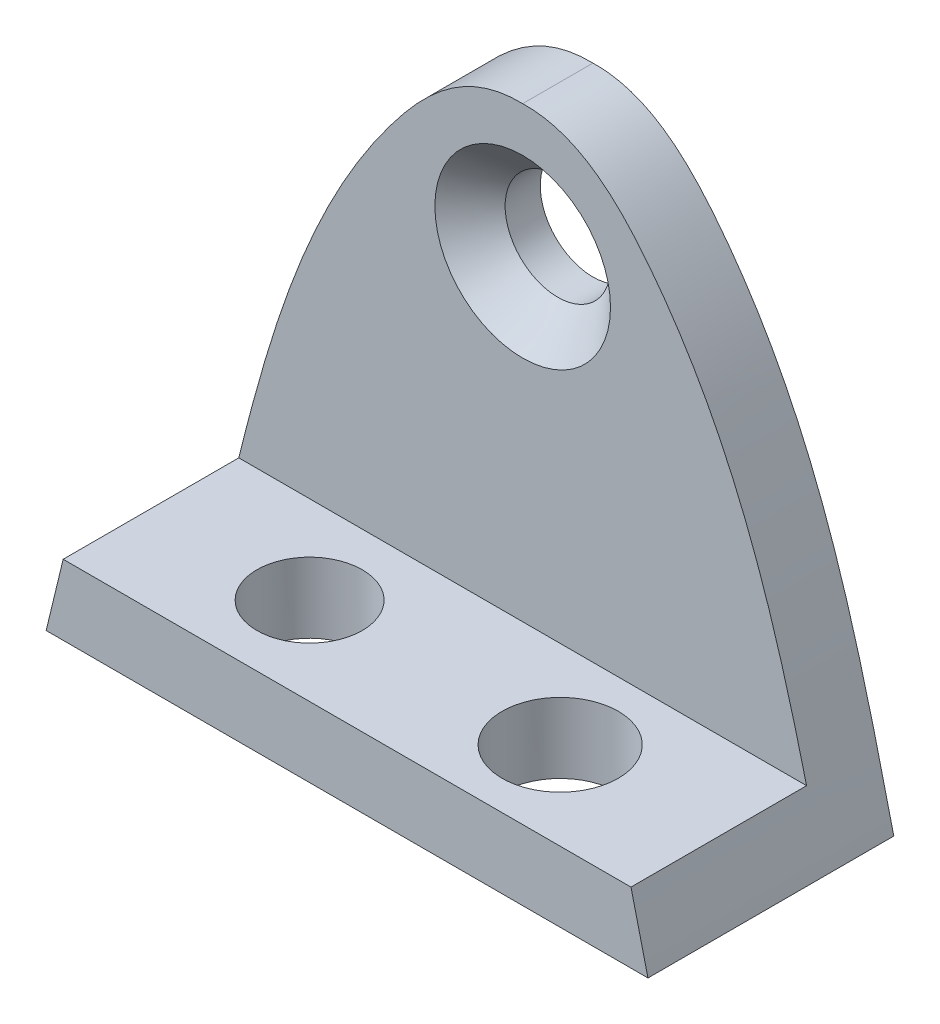
SolidWorks part; units mm, degrees
ref_plane "Front Plane" through (0, 0, 0) normal (0, 0, 1) x (1, 0, 0)
ref_plane "Top Plane" through (0, 0, 0) normal (0, 1, 0) x (1, 0, 0)
ref_plane "Right Plane" through (0, 0, 0) normal (1, 0, 0) x (0, 0, -1)
sketch "Sketch1" plane through (0, 0, 0) normal (0, 0, 1) x (1, 0, 0)
  line L0 (0, -1.5) -> (-1.5, -1.5) construction
  line L1 (0, -11) -> (-1.5, -11) construction
  line L2 (8.5669, -11) -> (-8.5669, -11)
  line L3 (0, 3.7746) -> (0, -11) construction
  circle A0 centre (0, 0) radius 1.5
  spline S0 degree 3 poles (0, 3.7746) (-1.6214, 3.8154) (-6.1428, -0.7192) (-7.5296, -6.6677) (-8.5669, -11) knots 0 0 0 0 0.251063 1 1 1 1
  spline S1 degree 3 poles (0, 3.7746) (1.6214, 3.8154) (6.1428, -0.7192) (7.5296, -6.6677) (8.5669, -11) knots 0 0 0 0 0.251063 1 1 1 1
  dimension "D1" = 9.5
extrude "Boss-Extrude1" add sketch "Sketch1" along normal blind 2
chamfer "Chamfer1" distance 1 angle 45 1 edges at (1.5, 0, 2)
sketch "Sketch2" plane through (0, 0, 2) normal (0, 0, 1) x (1, 0, 0)
  line L0 (-8.0829, -9) -> (8.0829, -9)
  line L1 (-8.5669, -11) -> (8.5669, -11) construction
  line L4 (-8.5669, -11) -> (8.5669, -11)
  spline S0 degree 3 poles (620.2924, -1897.1333) (47.5435, 18.092) (-101.7604, 11.144) (149.2414, -176.357) (-1823.8538, 825.5823) knots -2.77244 -2.77244 -2.77244 -2.77244 0.251063 8.528168 8.528168 8.528168 8.528168 only from (0, 3.7746) to (-8.5669, -11) construction
  spline S2 degree 3 poles (1823.843, 825.5768) (-149.2408, -176.3565) (101.7597, 11.1436) (-47.5429, 18.092) (-620.2788, -1897.088) knots -7.528153 -7.528153 -7.528153 -7.528153 0.748937 3.772416 3.772416 3.772416 3.772416 only from (8.5669, -11) to (0, 3.7746) construction
  spline S4 degree 3 poles (-8.0829, -9) (-8.2485, -9.6673) (-8.4077, -10.3351) (-8.5669, -11) knots 0.885061 0.885061 0.885061 0.885061 1 1 1 1
  spline S5 degree 3 poles (8.5669, -11) (8.4077, -10.3351) (8.2485, -9.6673) (8.0829, -9) knots 0 0 0 0 0.114939 0.114939 0.114939 0.114939
  dimension "D1" = 2
extrude "Boss-Extrude2" add sketch "Sketch2" along normal blind 5
sketch "Sketch3" plane through (0, -11, 0) normal (0, -1, 0) x (1, 0, 0)
  line L0 (-8.5669, 7) -> (8.5669, 7) construction
  line L1 (-3.5669, 4.5) -> (3.5669, 4.5) construction
  line L2 (-8.5669, 7) -> (-8.5669, 0) construction
  circle A0 centre (-3.5669, 4.5) radius 1.5
  circle A1 centre (3.5669, 4.5) radius 1.654
  point P6 (0, 4.5)
  point P7 (0, 7)
  dimension "D1" = 2.5
  dimension "D2" = 5
extrude "Cut-Extrude1" cut sketch "Sketch3" against normal through all
